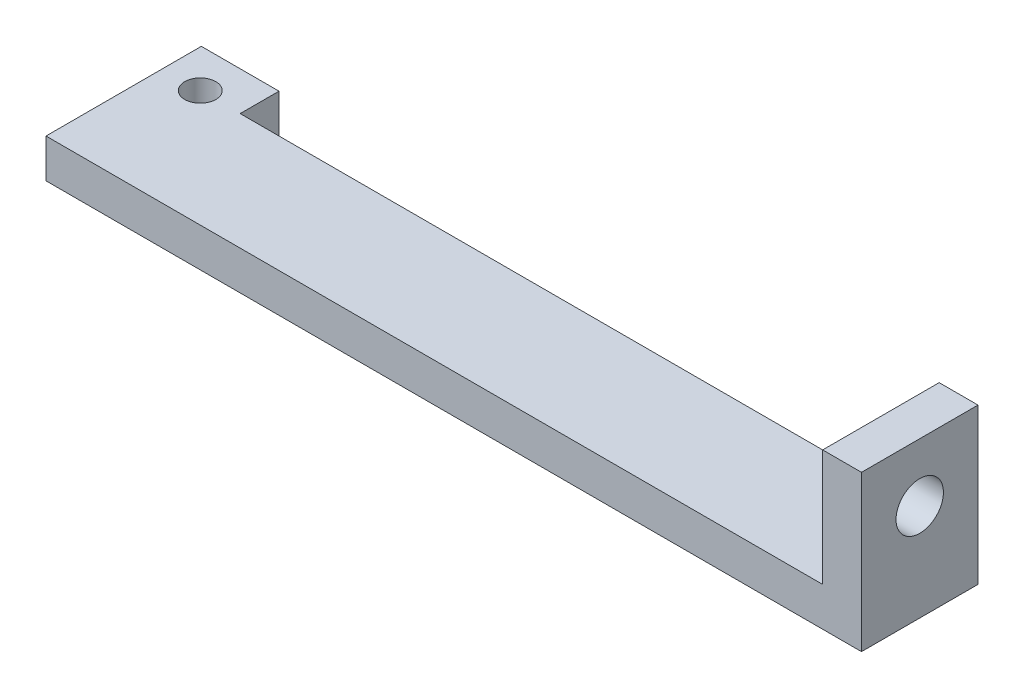
SolidWorks part; units mm, degrees
ref_plane "Front Plane" through (0, 0, 0) normal (0, 0, 1) x (1, 0, 0)
ref_plane "Top Plane" through (0, 0, 0) normal (0, 1, 0) x (1, 0, 0)
ref_plane "Right Plane" through (0, 0, 0) normal (1, 0, 0) x (0, 0, -1)
sketch "Sketch2" plane through (0, 0, 0) normal (0, 1, 0) x (1, 0, 0)
  line L1 (0, 0) -> (48.26, 0)
  line L2 (0, 0) -> (0, 7.62)
  line L3 (0, 7.62) -> (48.26, 7.62)
  line L4 (48.26, 0) -> (48.26, 7.62)
  dimension "D1" = 48.26
  dimension "D2" = 7.62
extrude "Boss-Extrude1" add sketch "Sketch2" along normal blind 2.54
sketch "Sketch3" plane through (0, 0, 0) normal (0, 1, 0) x (1, 0, 0)
  line L1 (0, 0) -> (-5.08, 0)
  line L2 (0, 0) -> (0, 10.16)
  line L3 (0, 10.16) -> (-5.08, 10.16)
  line L4 (-5.08, 0) -> (-5.08, 10.16)
  dimension "D1" = 10.16
  dimension "D2" = 5.08
extrude "Boss-Extrude2" add sketch "Sketch3" along normal blind 2.54
sketch "Sketch4" plane through (0, 2.54, 0) normal (0, 1, 0) x (1, 0, 0)
  line L0 (0, 10.16) -> (-5.08, 10.16) construction
  line L1 (-5.08, 10.16) -> (-5.08, 0) construction
  circle A0 centre (-2.6085, 7.62) radius 1.016
  dimension "D1" = 2.54
  dimension "D2" = 2.032
  dimension "D3" = 2.4715
extrude "Cut-Extrude1" cut sketch "Sketch4" against normal blind 2.54
ref_plane "Plane1" through (48.26, 0, 0) normal (-1, 0, 0) x (0, 0, 1)
sketch "Sketch5" plane through (48.26, 0, 0) normal (-1, 0, 0) x (0, 0, 1)
  line L0 (0, 2.54) -> (-7.62, 2.54)
  line L1 (-7.62, 2.54) -> (-7.62, 10.16)
  line L2 (-7.62, 10.16) -> (0, 10.16)
  line L3 (0, 10.16) -> (0, 2.54)
  line L4 (0, 2.54) -> (-7.62, 2.54) construction
  point P4 (-5.08, 7.62)
  point P7 (0, 7.62)
  point P10 (-3.81, 2.54)
  point P11 (-3.81, 2.54)
  dimension "D1" = 7.62
  dimension "D2" = 7.62
extrude "Boss-Extrude3" add sketch "Sketch5" along normal blind 2.54
sketch "Sketch7" plane through (45.72, 0, 0) normal (-1, 0, 0) x (0, 0, 1)
  line L1 (0, 10.16) -> (-7.62, 10.16) construction
  line L2 (-7.62, 10.16) -> (-7.62, 2.54) construction
  circle A0 centre (-3.81, 6.35) radius 1.55
  point P4 (-3.81, 10.16)
  point P7 (-7.62, 6.35)
  dimension "D1" = 3.1
extrude "Cut-Extrude2" cut sketch "Sketch7" against normal blind 2.54
